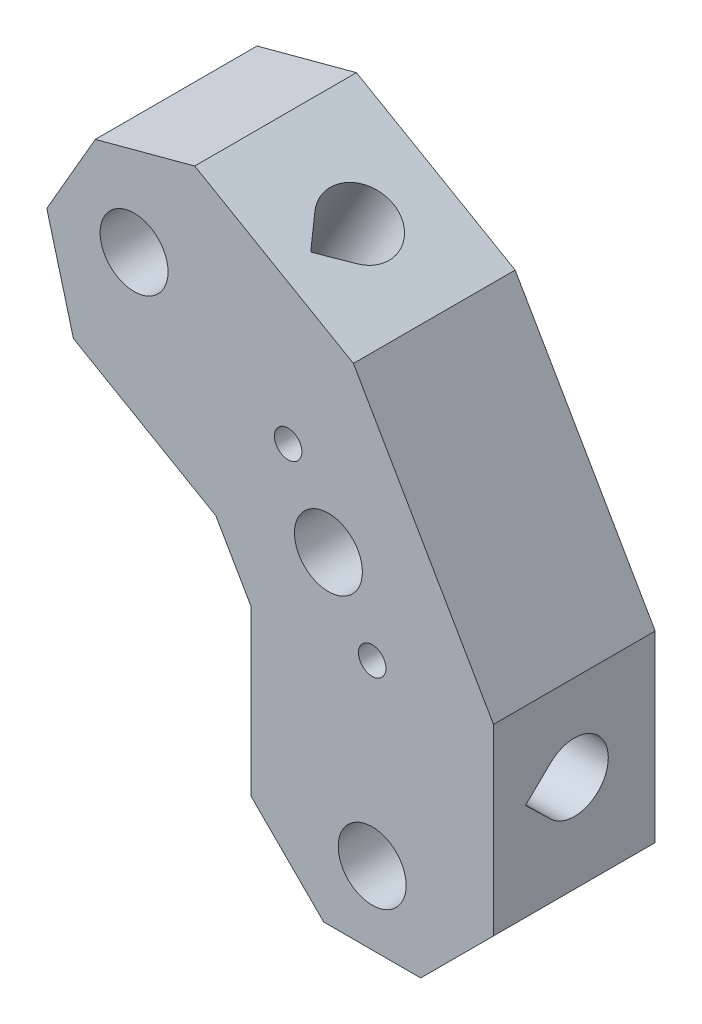
SolidWorks part; units mm, degrees
ref_plane "Front Plane" through (0, 0, 0) normal (0, 0, 1) x (1, 0, 0)
ref_plane "Top Plane" through (0, 0, 0) normal (0, 1, 0) x (1, 0, 0)
ref_plane "Right Plane" through (0, 0, 0) normal (1, 0, 0) x (0, 0, -1)
ref_plane "Plane1" through (0, 0, 20) normal (0, 0, 1) x (1, 0, 0)
sketch "Sketch1" plane through (0, 0, 20) normal (0, 0, 1) x (1, 0, 0)
  line L0 (15, -34) -> (15, -11.3397)
  line L1 (15, -11.3397) -> (-2.3205, 18.6603)
  line L2 (-2.3205, 18.6603) -> (-21.9449, 29.9904)
  line L3 (-21.9449, 29.9904) -> (-42.4352, 24.5)
  line L4 (-42.4352, 24.5) -> (-36.9449, 4.0096)
  line L5 (-36.9449, 4.0096) -> (-15, -8.6603)
  line L6 (-15, -8.6603) -> (-15, -34)
  line L7 (-15, -34) -> (0, -49)
  line L8 (0, -49) -> (15, -34)
extrude "Boss-Extrude1" add sketch "Sketch1" against normal blind 20
sketch "Sketch2" plane through (-7.5, -12.9904, 0) normal (-0.5, -0.866, 0) x (0.866, -0.5, 0)
  line L0 (-18.9788, 12.9176) -> (-22, 16.0461)
  line L1 (-22, 16.0461) -> (-25.0212, 12.9176)
  arc A0 (-25.0212, 12.9176) -> (-18.9788, 12.9176) centre (-22, 10) ccw
extrude "Cut-Extrude1" cut sketch "Sketch2" against normal through all
sketch "Sketch3" plane through (15, 0, 0) normal (1, 0, 0) x (0, 0, -1)
  line L0 (-12.9176, -18.9788) -> (-16.0461, -22)
  line L1 (-16.0461, -22) -> (-12.9176, -25.0212)
  arc A0 (-12.9176, -25.0212) -> (-12.9176, -18.9788) centre (-10, -22) ccw
extrude "Cut-Extrude2" cut sketch "Sketch3" against normal through all
hole_wizard "Hole1" positions "Sketch5" profile "Sketch4" legacy
sketch "Sketch5" plane through (0, 0, 20) normal (0, 0, 1) x (1, 0, 0)
  point P0 (0, -12)
sketch "Sketch4" plane through (0, -12, 20) normal (1, 0, 0) x (0, -1, 0)
  line L0 (0, 0) -> (0, 20)
  line L1 (0, 20) -> (1.7, 20)
  line L2 (1.7, 20) -> (1.7, 0)
  line L3 (1.7, 0) -> (0, 0)
  line L4 (0, 110) -> (0, -10) construction
  dimension "Diameter" = 3.4
  dimension "Depth" = 20
hole_wizard "Hole2" positions "Sketch7" profile "Sketch6" legacy
sketch "Sketch7" plane through (0, 0, 20) normal (0, 0, 1) x (1, 0, 0)
  point P0 (-10.3923, 6)
sketch "Sketch6" plane through (-10.3923, 6, 20) normal (1, 0, 0) x (0, -1, 0)
  line L0 (0, 0) -> (0, 20)
  line L1 (0, 20) -> (1.7, 20)
  line L2 (1.7, 20) -> (1.7, 0)
  line L3 (1.7, 0) -> (0, 0)
  line L4 (0, 110) -> (0, -10) construction
  dimension "Diameter" = 3.4
  dimension "Depth" = 20
hole_wizard "Hole3" positions "Sketch9" profile "Sketch8" legacy
sketch "Sketch9" plane through (0, 0, 20) normal (0, 0, 1) x (1, 0, 0)
  point P0 (-5.4127, -3.125)
sketch "Sketch8" plane through (-5.4127, -3.125, 20) normal (1, 0, 0) x (0, -1, 0)
  line L0 (0, 0) -> (0, 20)
  line L1 (0, 20) -> (4.2, 20)
  line L2 (4.2, 20) -> (4.2, 0)
  line L3 (4.2, 0) -> (0, 0)
  line L4 (0, 110) -> (0, -10) construction
  dimension "Diameter" = 8.4
  dimension "Depth" = 20
hole_wizard "Hole4" positions "Sketch11" profile "Sketch10" legacy
sketch "Sketch11" plane through (0, 0, 20) normal (0, 0, 1) x (1, 0, 0)
  point P0 (-29.4449, 17)
sketch "Sketch10" plane through (-29.4449, 17, 20) normal (1, 0, 0) x (0, -1, 0)
  line L0 (0, 0) -> (0, 20)
  line L1 (0, 20) -> (4.2, 20)
  line L2 (4.2, 20) -> (4.2, 0)
  line L3 (4.2, 0) -> (0, 0)
  line L4 (0, 110) -> (0, -10) construction
  dimension "Diameter" = 8.4
  dimension "Depth" = 20
hole_wizard "Hole5" positions "Sketch13" profile "Sketch12" legacy
sketch "Sketch13" plane through (0, 0, 20) normal (0, 0, 1) x (1, 0, 0)
  point P0 (0, -34)
sketch "Sketch12" plane through (0, -34, 20) normal (1, 0, 0) x (0, -1, 0)
  line L0 (0, 0) -> (0, 20)
  line L1 (0, 20) -> (4.2, 20)
  line L2 (4.2, 20) -> (4.2, 0)
  line L3 (4.2, 0) -> (0, 0)
  line L4 (0, 110) -> (0, -10) construction
  dimension "Diameter" = 8.4
  dimension "Depth" = 20
chamfer "Chamfer1" distance 8.4853 angle 45 1 edges at (-42.4352, 24.5, 10)
chamfer "Chamfer2" distance 5 angle 30 1 edges at (-15, -8.6603, 10)
chamfer "Chamfer3" distance 8.4853 angle 45 1 edges at (0, -49, 10)
